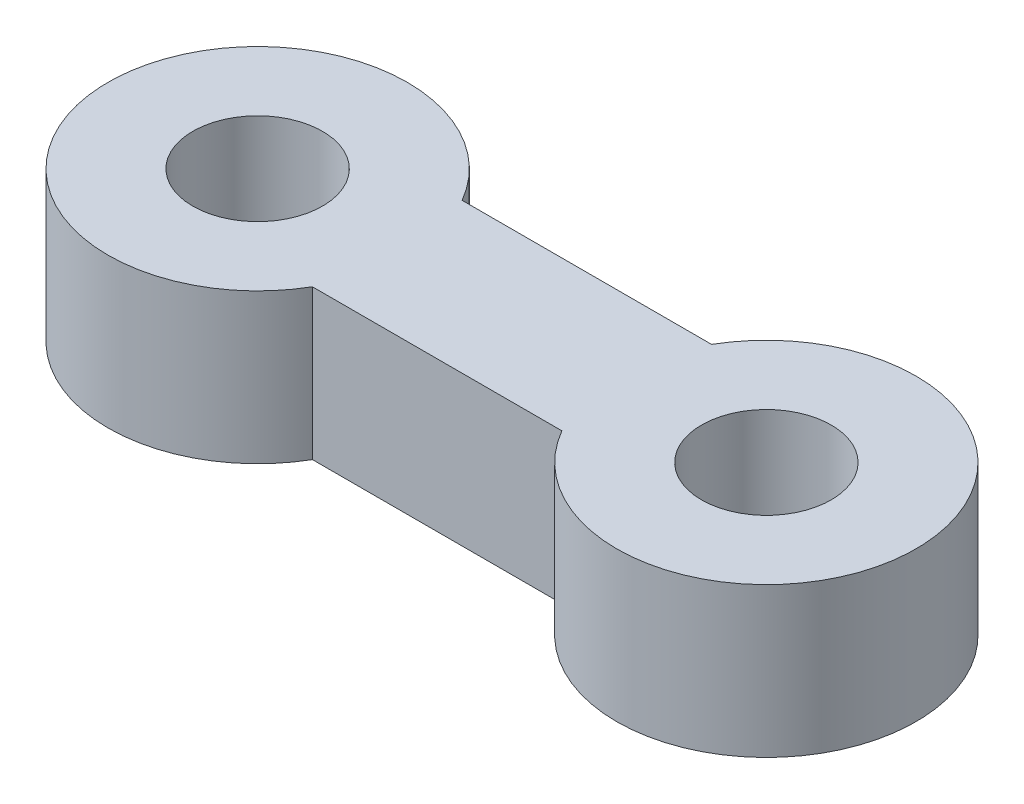
SolidWorks part; units mm, degrees
material "ABS"
ref_plane "Front Plane" through (0, 0, 0) normal (0, 0, 1) x (1, 0, 0)
ref_plane "Top Plane" through (0, 0, 0) normal (0, 1, 0) x (1, 0, 0)
ref_plane "Right Plane" through (0, 0, 0) normal (1, 0, 0) x (0, 0, -1)
sketch "Sketch1" plane through (0, 0, 0) normal (0, 1, 0) x (1, 0, 0)
  line L0 (0, 0) -> (10.1962, 0) construction
  line L1 (2.5981, 1.5) -> (7.5981, 1.5)
  line L2 (2.5981, -1.5) -> (7.5981, -1.5)
  arc A0 (2.5981, 1.5) -> (2.5981, -1.5) centre (0, 0) ccw
  circle A1 centre (0, 0) radius 1.3
  circle A2 centre (10.1962, 0) radius 1.3
  arc A3 (7.5981, -1.5) -> (7.5981, 1.5) centre (10.1962, 0) ccw
  dimension "D1" = 6
  dimension "D2" = 2.6
  dimension "D3" = 2.6
  dimension "D4" = 6
  dimension "D5" = 1.5
  dimension "D6" = 1.5
  dimension "D7" = 5
extrude "Boss-Extrude1" add sketch "Sketch1" along normal blind 3
